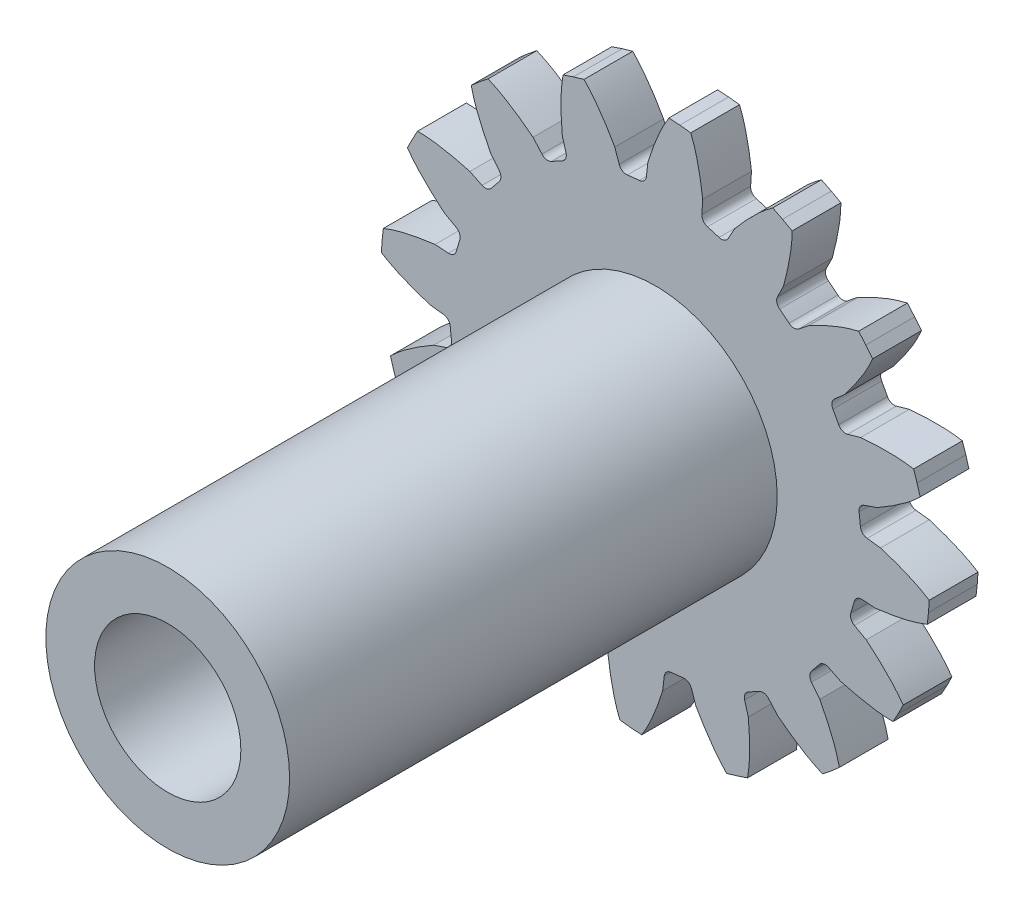
SolidWorks part; units mm, degrees
ref_plane "Front Plane" through (0, 0, 0) normal (0, 0, 1) x (1, 0, 0)
ref_plane "Top Plane" through (0, 0, 0) normal (0, 1, 0) x (1, 0, 0)
ref_plane "Right Plane" through (0, 0, 0) normal (1, 0, 0) x (0, 0, -1)
sketch "Sketch1" plane through (0, 0, 0) normal (0, 0, 1) x (1, 0, 0)
  circle A0 centre (0, 0) radius 10
  circle A1 centre (0, 0) radius 8.4375
  circle A2 centre (0, 0) radius 11.25
  circle A3 centre (0, 0) radius 8.5925
  circle A4 centre (0, 0) radius 100
sketch "Sketch2" plane through (0, 0, 0) normal (0, 0, 1) x (1, 0, 0)
  line L0 (0, 0) -> (0, 16.2403) construction
  line L1 (0, 0) -> (3.8268, 9.2388) construction
  line L2 (3.8268, 9.2388) -> (6.4557, 15.5853) construction
  line L3 (-0.3026, 9.2388) -> (-0.3962, 8.4282)
  line L4 (0, 0) -> (1.0067, 11.2049) construction
  line L5 (1.9446, 9.0369) -> (1.8922, 8.2226)
  line L6 (3.2559, 8.6513) -> (2.8592, 7.9383)
  line L7 (0, 0) -> (5.218, 9.9667) construction
  line L8 (5.2548, 7.6048) -> (4.8948, 6.8726)
  line L9 (6.3188, 6.7468) -> (5.6794, 6.2398)
  line L10 (7.7651, 5.015) -> (7.1522, 4.4762)
  line L11 (8.4197, 3.8151) -> (7.635, 3.5914)
  line L12 (9.0932, 1.6617) -> (8.3208, 1.3985)
  line L13 (9.2388, 0.3026) -> (8.4282, 0.3962)
  line L14 (9.0369, -1.9446) -> (8.2226, -1.8922)
  line L15 (8.6513, -3.2559) -> (7.9383, -2.8592)
  line L16 (7.6048, -5.2548) -> (6.8726, -4.8948)
  line L17 (6.7468, -6.3188) -> (6.2398, -5.6794)
  line L18 (5.015, -7.7651) -> (4.4762, -7.1522)
  line L19 (3.8151, -8.4197) -> (3.5914, -7.635)
  line L20 (1.6617, -9.0932) -> (1.3985, -8.3208)
  line L21 (0.3026, -9.2388) -> (0.3962, -8.4282)
  line L22 (-1.9446, -9.0369) -> (-1.8922, -8.2226)
  line L23 (-3.2559, -8.6513) -> (-2.8592, -7.9383)
  line L24 (-5.2548, -7.6048) -> (-4.8948, -6.8726)
  line L25 (-6.3188, -6.7468) -> (-5.6794, -6.2398)
  line L26 (-7.7651, -5.015) -> (-7.1522, -4.4762)
  line L27 (-8.4197, -3.8151) -> (-7.635, -3.5914)
  line L28 (-9.0932, -1.6617) -> (-8.3208, -1.3985)
  line L29 (-9.2388, -0.3026) -> (-8.4282, -0.3962)
  line L30 (-9.0369, 1.9446) -> (-8.2226, 1.8922)
  line L31 (-8.6513, 3.2559) -> (-7.9383, 2.8592)
  line L32 (-7.6048, 5.2548) -> (-6.8726, 4.8948)
  line L33 (-6.7468, 6.3188) -> (-6.2398, 5.6794)
  line L34 (-5.015, 7.7651) -> (-4.4762, 7.1522)
  line L35 (-3.8151, 8.4197) -> (-3.5914, 7.635)
  line L36 (-1.6617, 9.0932) -> (-1.3985, 8.3208)
  arc A0 (0, 10) -> (3.8268, 9.2388) centre (0, 0) cw
  circle A1 centre (0, 0) radius 10 construction
  circle A2 centre (0, 0) radius 11.25 construction
  circle A3 centre (0, 0) radius 8.4375 construction
  spline S0 degree 3 poles (-0.3026, 9.2388) (-0.0851, 9.9279) (0.1696, 10.6213) (0.5574, 11.2362) knots 0 0 0 0 1 1 1 1
  spline S1 degree 1 poles (0.5574, 11.2362) (1.0067, 11.2049) knots 0 0 1 1
  spline S2 degree 3 poles (1.9446, 9.0369) (1.8533, 9.7537) (1.7263, 10.4814) (1.4544, 11.1556) knots 0 0 0 0 1 1 1 1
  spline S3 degree 1 poles (1.4544, 11.1556) (1.0067, 11.2049) knots 0 0 1 1
  spline S4 degree 3 poles (3.2559, 8.6513) (3.721, 9.2044) (4.2213, 9.7479) (4.8148, 10.1676) knots 0 0 0 0 1 1 1 1
  spline S5 degree 1 poles (4.8148, 10.1676) (5.218, 9.9667) knots 0 0 1 1
  spline S6 degree 1 poles (5.6127, 9.7499) (5.218, 9.9667) knots 0 0 1 1
  spline S7 degree 3 poles (5.2548, 7.6048) (5.4443, 8.3021) (5.606, 9.0229) (5.6127, 9.7499) knots 0 0 0 0 1 1 1 1
  spline S8 degree 2 poles (1.8922, 8.2226) (2.3842, 8.1093) (2.8592, 7.9383) knots 0 0 0 1 1 1
  spline S9 degree 2 poles (4.8948, 6.8726) (5.306, 6.5797) (5.6794, 6.2398) knots 0 0 0 1 1 1
  spline S10 degree 3 poles (6.3188, 6.7468) (6.9599, 7.0802) (7.6303, 7.3904) (8.3393, 7.5511) knots 0 0 0 0 1 1 1 1
  spline S11 degree 1 poles (8.3393, 7.5511) (8.6349, 7.2112) knots 0 0 1 1
  spline S12 degree 1 poles (8.9166, 6.8598) (8.6349, 7.2112) knots 0 0 1 1
  spline S13 degree 3 poles (7.7651, 5.015) (8.2074, 5.5864) (8.6322, 6.1908) (8.9166, 6.8598) knots 0 0 0 0 1 1 1 1
  spline S14 degree 2 poles (7.1522, 4.4762) (7.4201, 4.0483) (7.635, 3.5914) knots 0 0 0 1 1 1
  spline S15 degree 3 poles (8.4197, 3.8151) (9.1396, 3.8773) (9.8777, 3.9079) (10.5942, 3.785) knots 0 0 0 0 1 1 1 1
  spline S16 degree 1 poles (10.5942, 3.785) (10.7372, 3.3579) knots 0 0 1 1
  spline S17 degree 1 poles (10.863, 2.9254) (10.7372, 3.3579) knots 0 0 1 1
  spline S18 degree 3 poles (9.0932, 1.6617) (9.7202, 2.0208) (10.3442, 2.4161) (10.863, 2.9254) knots 0 0 0 0 1 1 1 1
  spline S19 degree 2 poles (8.3208, 1.3985) (8.4044, 0.9007) (8.4282, 0.3962) knots 0 0 0 1 1 1
  spline S20 degree 3 poles (9.2388, 0.3026) (9.9279, 0.0851) (10.6213, -0.1696) (11.2362, -0.5574) knots 0 0 0 0 1 1 1 1
  spline S21 degree 1 poles (11.2362, -0.5574) (11.2049, -1.0067) knots 0 0 1 1
  spline S22 degree 1 poles (11.1556, -1.4544) (11.2049, -1.0067) knots 0 0 1 1
  spline S23 degree 3 poles (9.0369, -1.9446) (9.7537, -1.8533) (10.4814, -1.7263) (11.1556, -1.4544) knots 0 0 0 0 1 1 1 1
  spline S24 degree 2 poles (8.2226, -1.8922) (8.1093, -2.3842) (7.9383, -2.8592) knots 0 0 0 1 1 1
  spline S25 degree 3 poles (8.6513, -3.2559) (9.2044, -3.721) (9.7479, -4.2213) (10.1676, -4.8148) knots 0 0 0 0 1 1 1 1
  spline S26 degree 1 poles (10.1676, -4.8148) (9.9667, -5.218) knots 0 0 1 1
  spline S27 degree 1 poles (9.7499, -5.6127) (9.9667, -5.218) knots 0 0 1 1
  spline S28 degree 3 poles (7.6048, -5.2548) (8.3021, -5.4443) (9.0229, -5.606) (9.7499, -5.6127) knots 0 0 0 0 1 1 1 1
  spline S29 degree 2 poles (6.8726, -4.8948) (6.5797, -5.306) (6.2398, -5.6794) knots 0 0 0 1 1 1
  spline S30 degree 3 poles (6.7468, -6.3188) (7.0802, -6.9599) (7.3904, -7.6303) (7.5511, -8.3393) knots 0 0 0 0 1 1 1 1
  spline S31 degree 1 poles (7.5511, -8.3393) (7.2112, -8.6349) knots 0 0 1 1
  spline S32 degree 1 poles (6.8598, -8.9166) (7.2112, -8.6349) knots 0 0 1 1
  spline S33 degree 3 poles (5.015, -7.7651) (5.5864, -8.2074) (6.1908, -8.6322) (6.8598, -8.9166) knots 0 0 0 0 1 1 1 1
  spline S34 degree 2 poles (4.4762, -7.1522) (4.0483, -7.4201) (3.5914, -7.635) knots 0 0 0 1 1 1
  spline S35 degree 3 poles (3.8151, -8.4197) (3.8773, -9.1396) (3.9079, -9.8777) (3.785, -10.5942) knots 0 0 0 0 1 1 1 1
  spline S36 degree 1 poles (3.785, -10.5942) (3.3579, -10.7372) knots 0 0 1 1
  spline S37 degree 1 poles (2.9254, -10.863) (3.3579, -10.7372) knots 0 0 1 1
  spline S38 degree 3 poles (1.6617, -9.0932) (2.0208, -9.7202) (2.4161, -10.3442) (2.9254, -10.863) knots 0 0 0 0 1 1 1 1
  spline S39 degree 2 poles (1.3985, -8.3208) (0.9007, -8.4044) (0.3962, -8.4282) knots 0 0 0 1 1 1
  spline S40 degree 3 poles (0.3026, -9.2388) (0.0851, -9.9279) (-0.1696, -10.6213) (-0.5574, -11.2362) knots 0 0 0 0 1 1 1 1
  spline S41 degree 1 poles (-0.5574, -11.2362) (-1.0067, -11.2049) knots 0 0 1 1
  spline S42 degree 1 poles (-1.4544, -11.1556) (-1.0067, -11.2049) knots 0 0 1 1
  spline S43 degree 3 poles (-1.9446, -9.0369) (-1.8533, -9.7537) (-1.7263, -10.4814) (-1.4544, -11.1556) knots 0 0 0 0 1 1 1 1
  spline S44 degree 2 poles (-1.8922, -8.2226) (-2.3842, -8.1093) (-2.8592, -7.9383) knots 0 0 0 1 1 1
  spline S45 degree 3 poles (-3.2559, -8.6513) (-3.721, -9.2044) (-4.2213, -9.7479) (-4.8148, -10.1676) knots 0 0 0 0 1 1 1 1
  spline S46 degree 1 poles (-4.8148, -10.1676) (-5.218, -9.9667) knots 0 0 1 1
  spline S47 degree 1 poles (-5.6127, -9.7499) (-5.218, -9.9667) knots 0 0 1 1
  spline S48 degree 3 poles (-5.2548, -7.6048) (-5.4443, -8.3021) (-5.606, -9.0229) (-5.6127, -9.7499) knots 0 0 0 0 1 1 1 1
  spline S49 degree 2 poles (-4.8948, -6.8726) (-5.306, -6.5797) (-5.6794, -6.2398) knots 0 0 0 1 1 1
  spline S50 degree 3 poles (-6.3188, -6.7468) (-6.9599, -7.0802) (-7.6303, -7.3904) (-8.3393, -7.5511) knots 0 0 0 0 1 1 1 1
  spline S51 degree 1 poles (-8.3393, -7.5511) (-8.6349, -7.2112) knots 0 0 1 1
  spline S52 degree 1 poles (-8.9166, -6.8598) (-8.6349, -7.2112) knots 0 0 1 1
  spline S53 degree 3 poles (-7.7651, -5.015) (-8.2074, -5.5864) (-8.6322, -6.1908) (-8.9166, -6.8598) knots 0 0 0 0 1 1 1 1
  spline S54 degree 2 poles (-7.1522, -4.4762) (-7.4201, -4.0483) (-7.635, -3.5914) knots 0 0 0 1 1 1
  spline S55 degree 3 poles (-8.4197, -3.8151) (-9.1396, -3.8773) (-9.8777, -3.9079) (-10.5942, -3.785) knots 0 0 0 0 1 1 1 1
  spline S56 degree 1 poles (-10.5942, -3.785) (-10.7372, -3.3579) knots 0 0 1 1
  spline S57 degree 1 poles (-10.863, -2.9254) (-10.7372, -3.3579) knots 0 0 1 1
  spline S58 degree 3 poles (-9.0932, -1.6617) (-9.7202, -2.0208) (-10.3442, -2.4161) (-10.863, -2.9254) knots 0 0 0 0 1 1 1 1
  spline S59 degree 2 poles (-8.3208, -1.3985) (-8.4044, -0.9007) (-8.4282, -0.3962) knots 0 0 0 1 1 1
  spline S60 degree 3 poles (-9.2388, -0.3026) (-9.9279, -0.0851) (-10.6213, 0.1696) (-11.2362, 0.5574) knots 0 0 0 0 1 1 1 1
  spline S61 degree 1 poles (-11.2362, 0.5574) (-11.2049, 1.0067) knots 0 0 1 1
  spline S62 degree 1 poles (-11.1556, 1.4544) (-11.2049, 1.0067) knots 0 0 1 1
  spline S63 degree 3 poles (-9.0369, 1.9446) (-9.7537, 1.8533) (-10.4814, 1.7263) (-11.1556, 1.4544) knots 0 0 0 0 1 1 1 1
  spline S64 degree 2 poles (-8.2226, 1.8922) (-8.1093, 2.3842) (-7.9383, 2.8592) knots 0 0 0 1 1 1
  spline S65 degree 3 poles (-8.6513, 3.2559) (-9.2044, 3.721) (-9.7479, 4.2213) (-10.1676, 4.8148) knots 0 0 0 0 1 1 1 1
  spline S66 degree 1 poles (-10.1676, 4.8148) (-9.9667, 5.218) knots 0 0 1 1
  spline S67 degree 1 poles (-9.7499, 5.6127) (-9.9667, 5.218) knots 0 0 1 1
  spline S68 degree 3 poles (-7.6048, 5.2548) (-8.3021, 5.4443) (-9.0229, 5.606) (-9.7499, 5.6127) knots 0 0 0 0 1 1 1 1
  spline S69 degree 2 poles (-6.8726, 4.8948) (-6.5797, 5.306) (-6.2398, 5.6794) knots 0 0 0 1 1 1
  spline S70 degree 3 poles (-6.7468, 6.3188) (-7.0802, 6.9599) (-7.3904, 7.6303) (-7.5511, 8.3393) knots 0 0 0 0 1 1 1 1
  spline S71 degree 1 poles (-7.5511, 8.3393) (-7.2112, 8.6349) knots 0 0 1 1
  spline S72 degree 1 poles (-6.8598, 8.9166) (-7.2112, 8.6349) knots 0 0 1 1
  spline S73 degree 3 poles (-5.015, 7.7651) (-5.5864, 8.2074) (-6.1908, 8.6322) (-6.8598, 8.9166) knots 0 0 0 0 1 1 1 1
  spline S74 degree 2 poles (-4.4762, 7.1522) (-4.0483, 7.4201) (-3.5914, 7.635) knots 0 0 0 1 1 1
  spline S75 degree 3 poles (-3.8151, 8.4197) (-3.8773, 9.1396) (-3.9079, 9.8777) (-3.785, 10.5942) knots 0 0 0 0 1 1 1 1
  spline S76 degree 1 poles (-3.785, 10.5942) (-3.3579, 10.7372) knots 0 0 1 1
  spline S77 degree 1 poles (-2.9254, 10.863) (-3.3579, 10.7372) knots 0 0 1 1
  spline S78 degree 3 poles (-1.6617, 9.0932) (-2.0208, 9.7202) (-2.4161, 10.3442) (-2.9254, 10.863) knots 0 0 0 0 1 1 1 1
  spline S79 degree 2 poles (-1.3985, 8.3208) (-0.9007, 8.4044) (-0.3962, 8.4282) knots 0 0 0 1 1 1
  point P215 (0, 0)
  dimension "D1" = 3.927
  dimension "D2" = 0.5574
  dimension "D3" = 0.5574
  dimension "D4" = 0.4476
  dimension "D5" = 0.4476
  dimension "D6" = 11.0632
  dimension "D7" = 11.0632
  dimension "D8" = 0.183
  dimension "D9" = 0.183
  dimension "D10" = 10.332
  dimension "D11" = 10.332
  dimension "D12" = 0.3026
  dimension "D13" = 0.3026
  dimension "D14" = 9.2438
  dimension "D15" = 9.2438
  dimension "D16" = 0.3962
  dimension "D17" = 0.3962
  dimension "D18" = 0.4504
  dimension "D19" = 0.4504
  dimension "D20" = 1.008
  dimension "D21" = 1.008
  dimension "D22" = 8
extrude "Boss-Extrude1" add sketch "Sketch2" along normal mid plane 20 contours L3 S79 L36 S78 S77 S76 S75 L35 S74 L34 S73 S72 S71 S70 L33 S69 L32 S68 S67 S66 S65 L31 S64 L30 S63 S62 S61 S60 L29 S59 L28 S58 S57 S56 S55 L27 S54 L26 S53 S52 S51 S50 L25 S49 L24 S48 S47 S46 S45 L23 S44 L22 S43 S42 S41 S40 L21 S39 L20 S38 S37 S36 S35 L19 S34 L18 S33 S32 S31 S30 L17 S29 L16 S28 S27 S26 S25 L15 S24 L14 S23 S22 S21 S20 L13 S19 L12 S18 S17 S16 S15 L11 S14 L10 S13 S12 S11 S10 L9 S9 L8 S7 S6 S5 S4 L6 S8 L5 S2 S3 S1 S0
ref_plane "Plane1" through (0, 0, 50) normal (0, 0, 1) x (1, 0, 0)
sketch "Sketch3" plane through (0, 0, 50) normal (0, 0, 1) x (1, 0, 0)
  circle A0 centre (0, 0) radius 12
fillet "Fillet1" radius 0.3125 32 edges at (-0.3962, 8.4282, 0) (-1.3985, 8.3208, 0) (-3.5914, 7.635, 0) (-4.4762, 7.1522, 0) (-6.2398, 5.6794, 0) (-6.8726, 4.8948, 0) (-7.9383, 2.8592, 0) (-8.2226, 1.8922, 0) (-8.4282, -0.3962, 0) (-8.3208, -1.3985, 0) (-7.635, -3.5914, 0) (-7.1522, -4.4762, 0) (-5.6794, -6.2398, 0) (-4.8948, -6.8726, 0) (-2.8592, -7.9383, 0) (-1.8922, -8.2226, 0) (0.3962, -8.4282, 0) (1.3985, -8.3208, 0) (3.5914, -7.635, 0) (4.4762, -7.1522, 0) (6.2398, -5.6794, 0) (6.8726, -4.8948, 0) (7.9383, -2.8592, 0) (8.2226, -1.8922, 0) (8.4282, 0.3962, 0) (8.3208, 1.3985, 0) (7.635, 3.5914, 0) (7.1522, 4.4762, 0) (4.8948, 6.8726, 0) (5.6794, 6.2398, 0) (1.8922, 8.2226, 0) (2.8592, 7.9383, 0)
ref_plane "Plane2" through (0, 0, 15) normal (0, 0, 1) x (1, 0, 0)
sketch "Sketch4" plane through (0, 0, 15) normal (0, 0, 1) x (1, 0, 0)
  circle A0 centre (0, 0) radius 12
sketch "Sketch5" plane through (0, 0, 10) normal (0, 0, 1) x (1, 0, 0)
  circle A0 centre (0, 0) radius 50
sketch "Sketch6" plane through (0, 0, 0) normal (1, 0, 0) x (0, 0, -1)
  line L0 (-15, 0) -> (-10, 0)
  line L1 (-15, 12) -> (-15, -12) construction
  line L2 (-10, 50) -> (-10, -50) construction
scale "Scale1" scale about origin uniform scaling no x scale factor 10 y scale factor 10 z scale factor 1
extrude "Boss-Extrude2" add sketch "Sketch5" along normal blind 200 contours A0
sketch "Sketch15" plane through (0, 0, 210) normal (0, 0, 1) x (1, 0, 0)
  circle A0 centre (0, 0) radius 30
extrude "Cut-Extrude1" cut sketch "Sketch15" against normal blind 200
